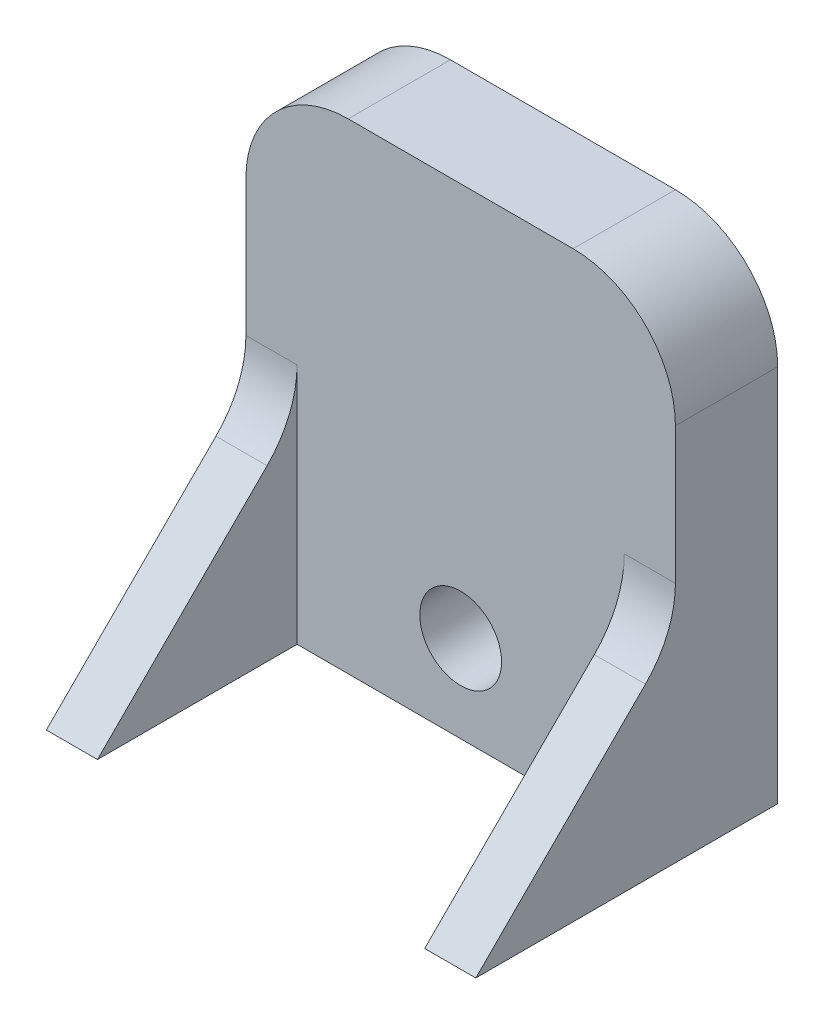
SolidWorks part; units mm, degrees
ref_plane "Front Plane" through (0, 0, 0) normal (0, 0, 1) x (1, 0, 0)
ref_plane "Top Plane" through (0, 0, 0) normal (0, 1, 0) x (1, 0, 0)
ref_plane "Right Plane" through (0, 0, 0) normal (1, 0, 0) x (0, 0, -1)
sketch "Sketch1" plane through (0, 0, 0) normal (0, 0, 1) x (1, 0, 0)
  line L4 (2.5551, 27.4807) -> (-39.4449, 27.4807)
  line L5 (-39.4449, 27.4807) -> (-39.4449, -19.5193)
  line L6 (-39.4449, -19.5193) -> (2.5551, -19.5193)
  line L7 (2.5551, -19.5193) -> (2.5551, 27.4807)
  line L8 (-7.4449, 27.4807) -> (-29.4449, 27.4807)
  line L9 (-39.4449, 17.4807) -> (-39.4449, -19.5193)
  line L10 (-39.4449, -19.5193) -> (2.5551, -19.5193)
  line L11 (2.5551, -19.5193) -> (2.5551, 17.4807)
  circle A0 centre (-18.4449, -11.0193) radius 4 construction
  circle A1 centre (-18.4449, -11.0193) radius 4
  arc A2 (2.5551, 17.4807) -> (-7.4449, 27.4807) centre (-7.4449, 17.4807) ccw
  arc A3 (-39.4449, 17.4807) -> (-29.4449, 27.4807) centre (-29.4449, 17.4807) cw
  dimension "D2" = 10
  dimension "D1" = 0
extrude "Boss-Extrude1" add sketch "Sketch1" against normal blind 10
sketch "Sketch2" plane through (-39.4449, 0, 0) normal (-1, 0, 0) x (0, 0, 1)
  line L0 (0, -19.5193) -> (19.5193, -19.5193)
  line L1 (19.5193, -19.5193) -> (0, 0)
  line L2 (0, 0) -> (0, -19.5193)
  dimension "D1" = 45
extrude "Boss-Extrude2" add sketch "Sketch2" against normal blind 5
fillet "Fillet1" radius 10 1 edges at (-36.9449, 0, 0)
ref_plane "Plane1" through (-18.4449, 0, 0) normal (1, 0, 0) x (0, 0, -1)
mirror "Mirror1" about plane through (-18.4449, 0, 0) normal (1, 0, 0) of "Fillet1", "Boss-Extrude2"
